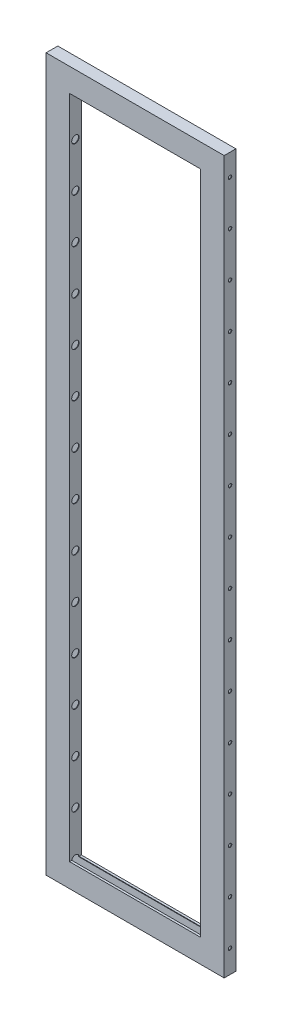
SolidWorks part; units mm, degrees
material "ASTM A36 Steel"
ref_plane "Front Plane" through (0, 0, 0) normal (0, 0, 1) x (1, 0, 0)
ref_plane "Top Plane" through (0, 0, 0) normal (0, 1, 0) x (1, 0, 0)
ref_plane "Right Plane" through (0, 0, 0) normal (1, 0, 0) x (0, 0, -1)
sketch "Sketch1" plane through (0, 0, 0) normal (0, 0, 1) x (1, 0, 0)
  line L1 (304, -1216) -> (-304, -1216)
  line L2 (304, -1216) -> (304, 1216)
  line L3 (304, 1216) -> (-304, 1216)
  line L4 (-304, -1216) -> (-304, 1216)
  line L5 (304, -1216) -> (-304, 1216) construction
  line L6 (304, 1216) -> (-304, -1216) construction
  point P0 (0, 0)
  dimension "D1" = 608
  dimension "D2" = 2432
sketch "Sketch2" plane through (0, 0, 0) normal (0, 1, 0) x (1, 0, 0)
  line L1 (-304, -20) -> (-224, -20)
  line L2 (-304, -20) -> (-304, 20)
  line L3 (-304, 20) -> (-224, 20)
  line L4 (-224, -20) -> (-224, 20)
  point P4 (-304, 0)
  dimension "D1" = 80
  dimension "D2" = 40
  dimension "D3" = 304
sweep "Sweep-Thin1" add profiles "Sketch2" path "Sketch1" parameters "D1"=2
sketch "Sketch3" plane through (224, 0, 0) normal (-1, 0, 0) x (0, 0, 1)
  line L0 (-20, 1136) -> (-20, -1136) construction
  line L2 (-20, 1216) -> (20, 1216) construction
  circle A0 centre (0, 1142) radius 12.5
  dimension "D2" = 25
  dimension "D3" = 74
  dimension "D1" = 20
extrude "Cut-Extrude1" cut sketch "Sketch3" against normal blind 10 and the other way blind 500
pattern_linear "LPattern1" count 16 spacing 152 along (0, -1, 0) of "Cut-Extrude1"
sketch "Sketch4" plane through (304, 0, 0) normal (1, 0, 0) x (0, 0, -1)
  line L0 (0, -1216) -> (0, 1216) construction
  line L2 (20, 1216) -> (-20, 1216) construction
  circle A0 centre (0, 1142) radius 6
  dimension "D1" = 12
  dimension "D2" = 74
extrude "Cut-Extrude2" cut sketch "Sketch4" against normal blind 10
pattern_linear "LPattern2" count 16 spacing 152 along (0, -1, 0) of "Cut-Extrude2"
